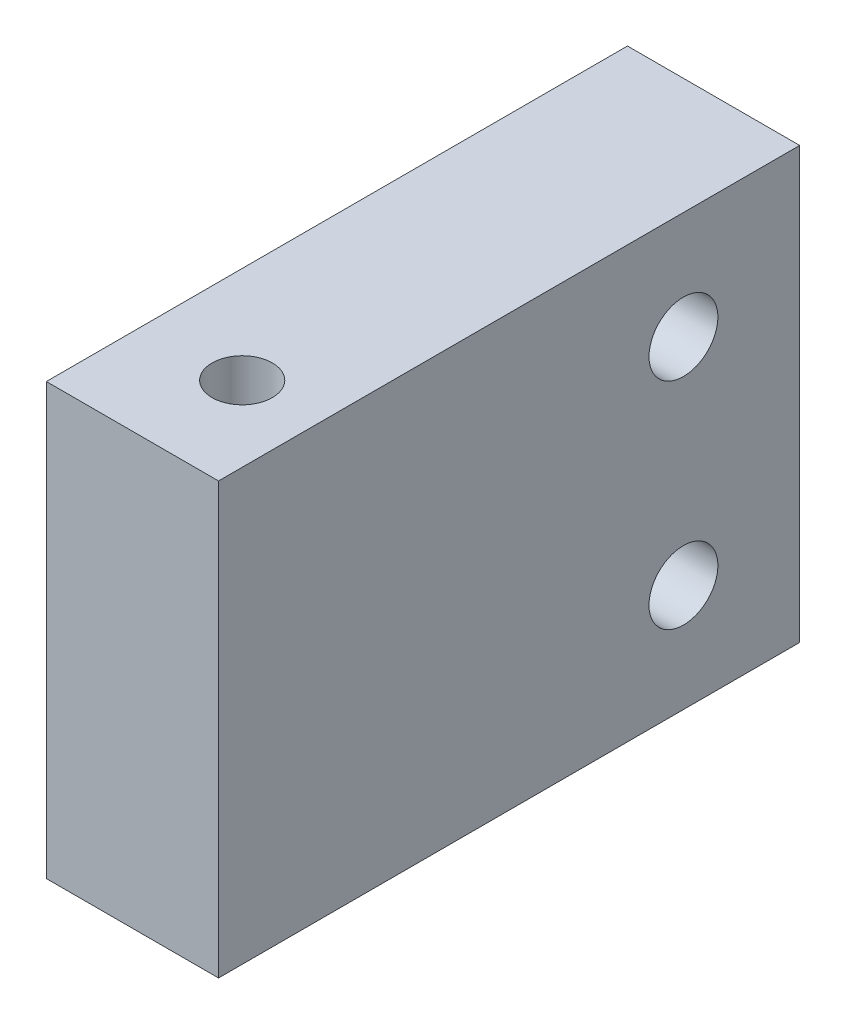
SolidWorks part; units mm, degrees
ref_plane "Front Plane" through (0, 0, 0) normal (0, 0, 1) x (1, 0, 0)
ref_plane "Top Plane" through (0, 0, 0) normal (0, 1, 0) x (1, 0, 0)
ref_plane "Right Plane" through (0, 0, 0) normal (1, 0, 0) x (0, 0, -1)
sketch "Sketch1" plane through (0, 0, 0) normal (0, 1, 0) x (1, 0, 0)
  line L0 (0, 16.9659) -> (0, 26.1146)
  line L1 (0, -21.6074) -> (0, 21.6074) construction
  line L2 (0, 26.1146) -> (-4.445, 26.1146)
  line L3 (0, 26.1146) -> (0, 41.6086)
  line L4 (0, 41.6086) -> (0, 45.6726)
  line L5 (0, 45.6726) -> (-10.16, 45.6726)
  line L6 (-10.16, 45.6726) -> (-10.16, 20.2726)
  line L7 (-10.16, 20.2726) -> (0, 20.2726)
  line L8 (0, 20.2726) -> (0, 45.6726)
  circle A0 centre (-4.445, 26.1146) radius 1.7768
  dimension "D1" = 4.445
  dimension "D2" = 4.064
  dimension "D3" = 15.494
  dimension "D4" = 10.16
  dimension "D5" = 25.4
extrude "Boss-Extrude1" add sketch "Sketch1" along normal blind 25.4
sketch "Sketch2" plane through (0, 0, -45.6726) normal (0, 0, -1) x (-1, 0, 0)
  line L0 (0, 25.4) -> (10.16, 25.4)
  line L1 (0, 13.97) -> (0, -13.97) construction
  line L2 (0, 25.4) -> (10.16, 25.4) construction
  line L3 (10.16, 25.4) -> (10.16, 0)
  line L4 (5.588, 0) -> (-5.588, 0) construction
  line L5 (10.16, 25.4) -> (10.16, 0) construction
  line L6 (10.16, 0) -> (0, 0)
  line L7 (0, 0) -> (0, 25.4)
extrude "Boss-Extrude2" add sketch "Sketch2" along normal blind 5.08
sketch "Sketch3" plane through (-10.16, 0, 0) normal (-1, 0, 0) x (0, 0, 1)
  line L0 (-50.7526, 19.05) -> (-45.6726, 19.05)
  line L1 (-50.7526, 0) -> (-50.7526, 25.4) construction
  line L2 (-47.7046, 17.018) -> (-47.7046, 8.382)
  line L3 (-47.7046, 17.018) -> (-47.7046, 8.382)
  line L4 (-50.7526, 12.7) -> (-47.7046, 12.7)
  circle A0 centre (-47.7046, 19.05) radius 2.032
  circle A2 centre (-47.7046, 6.35) radius 2.032
  dimension "D2" = 4.064
  dimension "D3" = 4.064
  dimension "D1" = 5.08
  dimension "D4" = 8.636
sketch "Sketch4" plane through (0, 0, -50.7526) normal (0, 0, -1) x (-1, 0, 0)
  line L1 (10.16, 25.4) -> (0, 25.4)
  line L2 (10.16, 25.4) -> (10.16, 0)
  line L3 (10.16, 0) -> (0, 0)
  line L4 (0, 25.4) -> (0, 0)
extrude "Boss-Extrude3" add sketch "Sketch4" along normal blind 3.81
extrude "Cut-Extrude1" cut sketch "Sketch3" against normal through all
